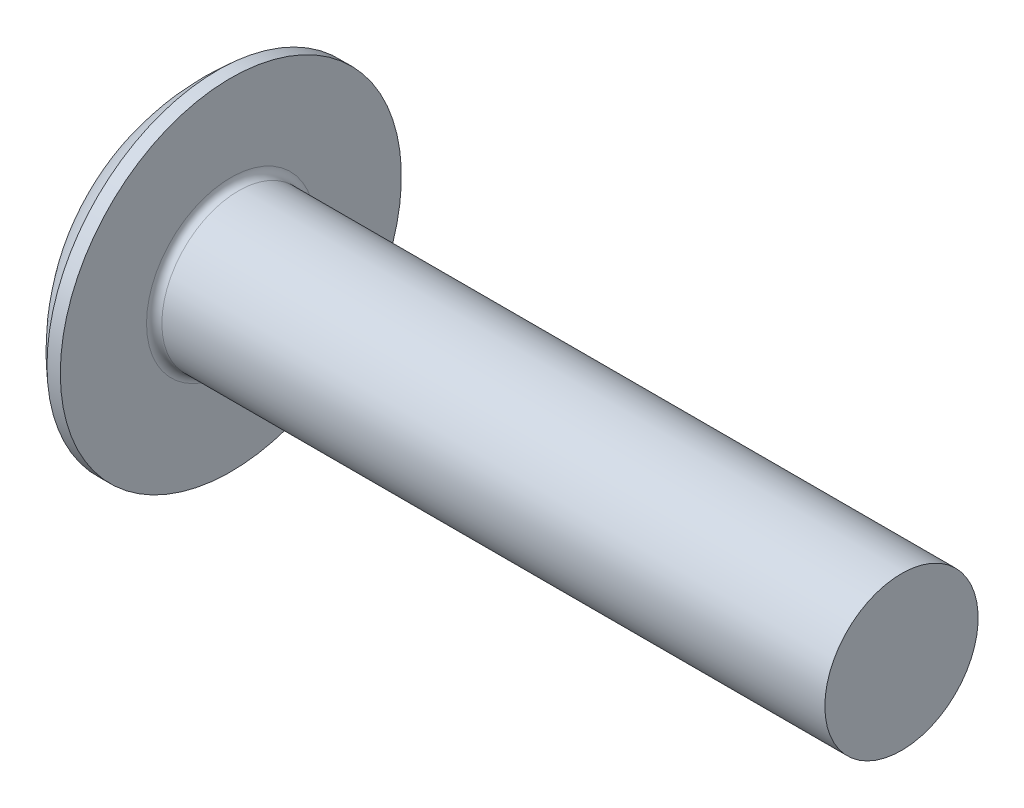
SolidWorks part; units mm, degrees
ref_plane "Plane1" through (0, 0, 0) normal (0, 0, 1) x (1, 0, 0)
ref_plane "Plane2" through (0, 0, 0) normal (0, 1, 0) x (1, 0, 0)
ref_plane "Plane3" through (0, 0, 0) normal (1, 0, 0) x (0, 0, -1)
sketch "BodySke" plane through (0, 0, 0) normal (0, 0, 1) x (1, 0, 0)
  line L0 (4.8, 4) -> (4.8, 8.9)
  line L1 (6.05, 6.35) -> (6.05, -3.175) construction
  line L2 (-25.4, 0) -> (127, 0) construction
  line L3 (39.8, 0) -> (0, 0)
  line L4 (4.8, 4) -> (39.8, 4)
  line L5 (39.8, 4) -> (39.8, 0)
  line L8 (9.8, 6.35) -> (9.8, -3.175) construction
  line L9 (4.8, 8.9) -> (4.1053, 8.9)
  arc A0 (4.1053, 8.9) -> (0, 0) centre (11.7, 0) ccw
  dimension "Oval_rad" = 11.7
  dimension "Length" = 35
  dimension "Head_ht" = 4.8
  dimension "Advance" = 1.25
  dimension "Thread_nom" = 30
  dimension "Diameter" = 8
  dimension "Head_dia" = 17.8
revolve "Base-Revolve" add sketch "BodySke"
cosmetic thread "ThreadCosmetic" [suppressed]
fillet "Fillet1" radius 0.4 1 edges at (4.8, 0, 4)
sketch "Sketch3" plane through (0, 0, 0) normal (1, 0, 0) x (0, 0, -1)
  line L0 (0.71, -3.9) -> (-0.71, -3.9)
  line L1 (0.71, -3.9) -> (0.71, 3.9)
  line L2 (-0.71, 3.9) -> (0.71, 3.9)
  line L3 (-0.71, 3.9) -> (-0.71, -3.9)
  dimension "Cross_dia" = 7.8
  dimension "D1" = 3.9
  dimension "Cross_width" = 1.42
  dimension "D2" = 0.71
ref_plane "Plane4" through (4.36, 0, 0) normal (1, 0, 0) x (0, 0, -1)
sketch "Sketch4" plane through (4.36, 0, 0) normal (1, 0, 0) x (0, 0, -1)
  line L0 (0.71, -1.7262) -> (-0.71, -1.7262)
  line L1 (0.71, -1.7262) -> (0.71, 1.7262)
  line L2 (-0.71, 1.7262) -> (0.71, 1.7262)
  line L3 (-0.71, 1.7262) -> (-0.71, -1.7262)
  dimension "D1" = 1.42
  dimension "D2" = 3.4524
  dimension "D3" = 0.71
  dimension "D4" = 1.7262
loft "Recess" cut profiles "Sketch3", "Sketch4"
pattern_circular "RecPat" count 2 every 90 about axis through (0, 0, 0) along (1, 0, 0) of "Recess"
sketch "RecCorSke" plane through (0, 0, 0) normal (0, 0, 1) x (1, 0, 0)
  line L0 (-3.175, 0) -> (15.875, 0) construction
  line L1 (-25.4, 0) -> (127, 0) construction
  line L2 (0, 0) -> (0, 1.5854)
  line L3 (0, 1.5854) -> (4.36, 1.2805)
  line L4 (4.36, 1.2805) -> (4.7761, 0)
  line L5 (4.7761, 0) -> (0, 0)
  dimension "Diameter" = 2.561
  dimension "Depth" = 4.36
  dimension "Draft_angle" = 4
  dimension "Bottom_angle" = 18
revolve "RecessCore" cut sketch "RecCorSke" angle 360 about L0
sketch "ThdSchSke" plane through (0, 0, 0) normal (0, 0, 1) x (1, 0, 0)
  line L0 (9.8, -3.3095) -> (9.3165, -4)
  line L1 (9.8, -3.3095) -> (10.2835, -4)
  line L2 (10.2835, -4) -> (10.2835, -5)
  line L3 (-3.175, 0) -> (5.1513, 0) construction
  line L5 (10.2835, -5) -> (9.3165, -5)
  line L6 (9.3165, -5) -> (9.3165, -4)
  dimension "Diameter" = 8
  dimension "SideAngle" = 55
  dimension "VeeAngle" = 70
  dimension "Thread_minor" = 6.619
  dimension "Overcut" = 10
  dimension "Start" = 9.8
revolve "ThreadSchematic" [suppressed] cut sketch "ThdSchSke" angle 360 about L3
pattern_linear "ThdSchPat" [suppressed]
equation "' \"Diameter@BodySke\" = 8"
equation "' \"Length@BodySke\" = 35"
equation "' \"Head_dia@BodySke\" = 17.8"
equation "' \"Oval_rad@BodySke\" = 11.7"
equation "' \"Head_ht@BodySke\" = 4.8"
equation "' \"Thread_nom@BodySke\" =  30"
equation "' \"Thread_nom@BodySke\" = 30"
equation "' \"Cross_dia@Sketch3\" = 7.8"
equation "' \"Cross_width@Sketch3\" = 1.42"
equation "' \"Cross_depth@Plane4\" = 4.36"
equation "' \"Diameter@RecCorSke\" = 2.561"
equation "' \"Radius@Fillet1\" = 0.4"
equation "' \"Thread_minor@ThreadCosmetic\" = 6.619"
equation "' \"Advance@BodySke\" = 1.25"
equation "\"D1@Sketch3\" = \"Cross_dia@Sketch3\" / 2"
equation "\"D2@Sketch3\" = \"Cross_width@Sketch3\" / 2"
equation "\"Depth@RecCorSke\" = \"Cross_depth@Plane4\""
equation "\"D1@Sketch4\" = \"Cross_width@Sketch3\""
equation "\"D2@Sketch4\" = \"Cross_dia@Sketch3\" - 2.0 * \"Cross_depth@Plane4\" * tan(26.5  * 0.017453292)"
equation "\"D3@Sketch4\" = \"D1@Sketch4\" / 2"
equation "\"D4@Sketch4\" = \"D2@Sketch4\" / 2"
equation "\"Thread_length@ThreadCosmetic\" = ((sgn( (\"Length@BodySke\" - \"Advance@BodySke\" * 2.0 ) - \"Thread_nom@BodySke\" )-1)*( (\"Length@BodySke\" - \"Advance@BodySke\" * 2.0 ) - \"Thread_nom@BodySke\" ))/-2+ \"Thread_nom@BodySke\""
equation "\"Thread_minor@ThdSchSke\" = \"Thread_minor@ThreadCosmetic\""
equation "\"Diameter@ThdSchSke\" = \"Diameter@BodySke\""
equation "\"Overcut@ThdSchSke\" = \"Diameter@BodySke\" * 1.25"
equation "\"Start@ThdSchSke\" = \"Head_ht@BodySke\" + \"Length@BodySke\" - \"Thread_length@ThreadCosmetic\"  '---Non-countersunk---"
equation "\"Num_threads@ThdSchPat\" = int( \"Thread_length@ThreadCosmetic\" / \"Advance@BodySke\" + 0.999 )  + 1"
equation "\"Advance@ThdSchPat\" = \"Thread_length@ThreadCosmetic\" /  (\"Num_threads@ThdSchPat\" - 1) 'relax it"
